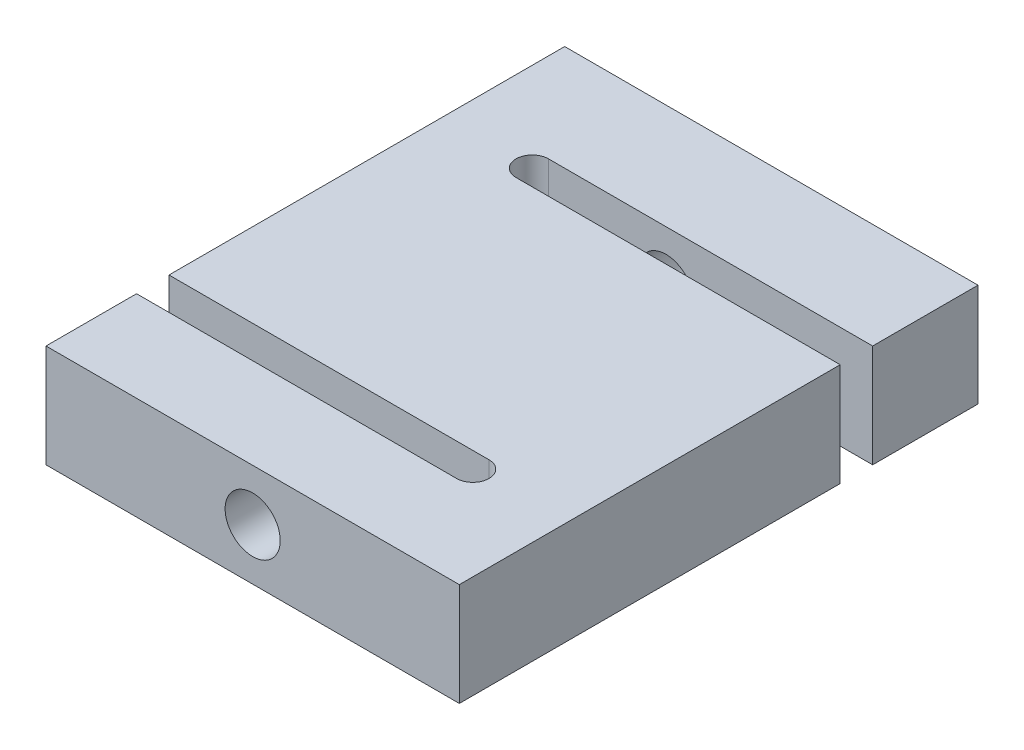
SolidWorks part; units mm, degrees
material "AISI 304"
ref_plane "前视基准面" through (0, 0, 0) normal (0, 0, 1) x (1, 0, 0)
ref_plane "上视基准面" through (0, 0, 0) normal (0, 1, 0) x (1, 0, 0)
ref_plane "右视基准面" through (0, 0, 0) normal (1, 0, 0) x (0, 0, -1)
sketch "草图1" plane through (0, 0, 0) normal (0, 1, 0) x (1, 0, 0)
  line L1 (-25.5, -32) -> (25.5, -32)
  line L2 (-25.5, -32) -> (-25.5, 32)
  line L3 (-25.5, 32) -> (25.5, 32)
  line L4 (25.5, -32) -> (25.5, 32)
  line L5 (-25.5, -32) -> (25.5, 32) construction
  line L6 (-25.5, 32) -> (25.5, -32) construction
  point P0 (0, 0)
  dimension "D1" = 64
  dimension "D2" = 51
extrude "凸台-拉伸1" add sketch "草图1" along normal mid plane 12.7
sketch "草图2" plane through (0, 6.35, 0) normal (0, 1, 0) x (1, 0, 0)
  line L0 (25.5, 17) -> (-14.5, 17) construction
  line L1 (25.5, -32) -> (25.5, 32) construction
  line L2 (25.5, 15) -> (-14.5, 15)
  line L3 (25.5, 19) -> (-14.5, 19)
  line L4 (25.5, 32) -> (-25.5, 32) construction
  arc A0 (25.5, 15) -> (25.5, 19) centre (25.5, 17) ccw
  arc A1 (-14.5, 19) -> (-14.5, 15) centre (-14.5, 17) ccw
  point P4 (5.5, 17)
  dimension "D2" = 2
  dimension "D1" = 15
  dimension "D3" = 40
extrude "切除-拉伸1" cut sketch "草图2" against normal through all
pattern_circular "阵列(圆周)1" count 2 over 360 about axis through (-0.2529, 0, 0.9125) along (0, 1, 0) of "切除-拉伸1"
sketch "草图3" plane through (0, 0, -32) normal (0, 0, -1) x (-1, 0, 0)
  point P0 (0, 0)
hole_wizard "M8 螺纹孔1" positions "草图3" profile "草图4" tap size "M8" standard "GB"
sketch "草图4" plane through (0, 0, -32) normal (1, 0, 0) x (0, 1, 0)
  line L0 (0, 0) -> (0, 13)
  line L1 (0, 13) -> (3.4, 13)
  line L2 (3.4, 13) -> (3.4, 0)
  line L5 (3.4, 0) -> (0, 0)
  line L11 (0, -6.35) -> (0, 107.95) construction
  dimension "通孔螺纹孔钻头直径" = 6.8
  dimension "通孔螺纹孔钻头深度" = 13
cosmetic thread "孔螺纹线1" parameters "D2"=8
mirror "镜向1" about plane through (0, 0, 0) normal (0, 0, 1) of "M8 螺纹孔1"
